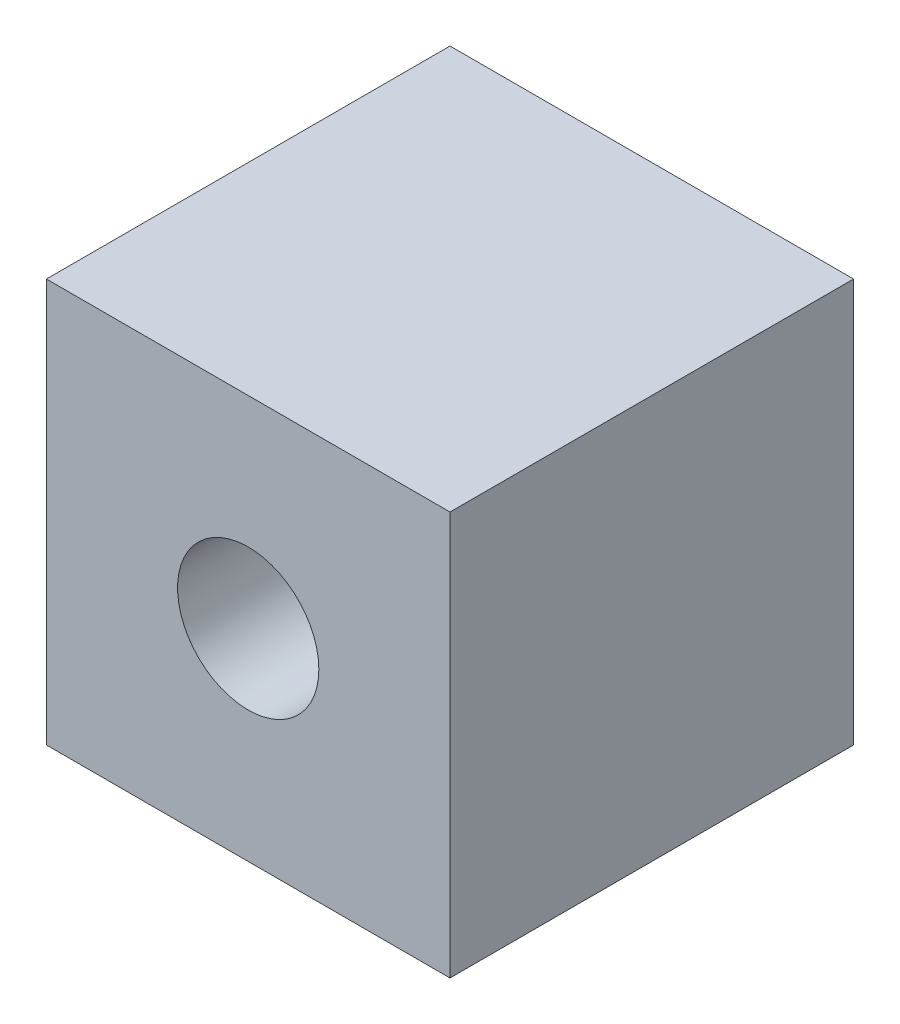
SolidWorks part; units mm, degrees
ref_plane "Front Plane" through (0, 0, 0) normal (0, 0, 1) x (1, 0, 0)
ref_plane "Top Plane" through (0, 0, 0) normal (0, 1, 0) x (1, 0, 0)
ref_plane "Right Plane" through (0, 0, 0) normal (1, 0, 0) x (0, 0, -1)
sketch "Sketch1" plane through (0, 0, 0) normal (0, 0, 1) x (1, 0, 0)
  line L0 (0, 5.08) -> (10.16, 5.08) construction
  line L1 (0, 0) -> (10.16, 0)
  line L2 (0, 0) -> (0, 10.16)
  line L3 (0, 10.16) -> (10.16, 10.16)
  line L4 (10.16, 0) -> (10.16, 10.16)
  circle A0 centre (5.08, 5.08) radius 1.778
  point P10 (5.08, 5.08)
  dimension "D2" = 3.556
  dimension "D1" = 10.16
extrude "Boss-Extrude1" add sketch "Sketch1" along normal blind 10.16
